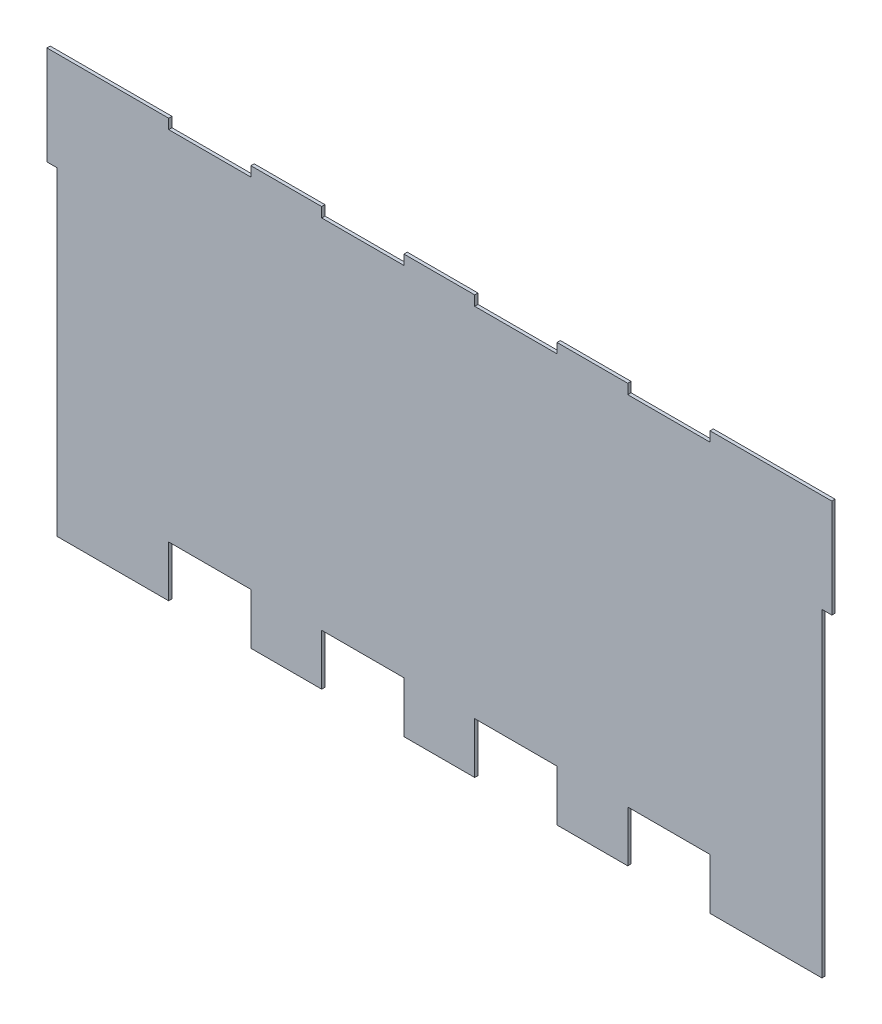
SolidWorks part; units mm, degrees
ref_plane "Front Plane" through (0, 0, 0) normal (0, 0, 1) x (1, 0, 0)
ref_plane "Top Plane" through (0, 0, 0) normal (0, 1, 0) x (1, 0, 0)
ref_plane "Right Plane" through (0, 0, 0) normal (1, 0, 0) x (0, 0, -1)
sketch "Sketch1" plane through (0, 0, 0) normal (0, 0, 1) x (1, 0, 0)
  line L1 (-232.5, -127) -> (232.5, -127)
  line L2 (-232.5, -127) -> (-232.5, 127)
  line L3 (-232.5, 127) -> (232.5, 127)
  line L4 (232.5, -127) -> (232.5, 127)
  line L5 (0, 127) -> (0, -127) construction
  line L6 (-232.5, 0) -> (232.5, 0) construction
  point P0 (0, 0)
  dimension "D1" = 465
  dimension "D2" = 254
extrude "Boss-Extrude1" add sketch "Sketch1" along normal blind 2
sketch "Sketch2" plane through (0, 0, 2) normal (0, 0, 1) x (1, 0, 0)
  line L0 (-232.5, -127) -> (232.5, -127) construction
  line L1 (-164.5, -133) -> (-114.5, -133)
  line L2 (-164.5, -133) -> (-164.5, -121)
  line L3 (-164.5, -121) -> (-114.5, -121)
  line L4 (-114.5, -133) -> (-114.5, -121)
  line L5 (-139.5, -121) -> (-139.5, -133) construction
  line L6 (-164.5, -127) -> (-114.5, -127) construction
  line L7 (232.5, 127) -> (-232.5, 127) construction
  line L8 (-71.5, -133) -> (-21.5, -133)
  line L9 (-71.5, -133) -> (-71.5, -121)
  line L10 (-71.5, -121) -> (-21.5, -121)
  line L11 (-21.5, -133) -> (-21.5, -121)
  line L12 (-46.5, -121) -> (-46.5, -133) construction
  line L13 (-71.5, -127) -> (-21.5, -127) construction
  line L14 (21.5, -133) -> (71.5, -133)
  line L15 (21.5, -133) -> (21.5, -121)
  line L16 (21.5, -121) -> (71.5, -121)
  line L17 (71.5, -133) -> (71.5, -121)
  line L18 (46.5, -121) -> (46.5, -133) construction
  line L19 (21.5, -127) -> (71.5, -127) construction
  line L20 (164.5, -133) -> (114.5, -133)
  line L21 (164.5, -133) -> (164.5, -121)
  line L22 (164.5, -121) -> (114.5, -121)
  line L23 (114.5, -133) -> (114.5, -121)
  line L24 (139.5, -121) -> (139.5, -133) construction
  line L25 (164.5, -127) -> (114.5, -127) construction
  line L26 (-164.5, 121) -> (-114.5, 121)
  line L27 (-164.5, 121) -> (-164.5, 133)
  line L28 (-164.5, 133) -> (-114.5, 133)
  line L29 (-114.5, 121) -> (-114.5, 133)
  line L30 (-139.5, 133) -> (-139.5, 121) construction
  line L31 (-164.5, 127) -> (-114.5, 127) construction
  line L33 (-71.5, 121) -> (-21.5, 121)
  line L34 (-71.5, 121) -> (-71.5, 133)
  line L35 (-71.5, 133) -> (-21.5, 133)
  line L36 (-21.5, 121) -> (-21.5, 133)
  line L37 (-46.5, 133) -> (-46.5, 121) construction
  line L38 (-71.5, 127) -> (-21.5, 127) construction
  line L39 (21.5, 121) -> (71.5, 121)
  line L40 (21.5, 121) -> (21.5, 133)
  line L41 (21.5, 133) -> (71.5, 133)
  line L42 (71.5, 121) -> (71.5, 133)
  line L43 (46.5, 133) -> (46.5, 121) construction
  line L44 (21.5, 127) -> (71.5, 127) construction
  line L45 (164.5, 121) -> (114.5, 121)
  line L46 (164.5, 121) -> (164.5, 133)
  line L47 (164.5, 133) -> (114.5, 133)
  line L48 (114.5, 121) -> (114.5, 133)
  line L49 (139.5, 133) -> (139.5, 121) construction
  line L50 (164.5, 127) -> (114.5, 127) construction
  point P0 (-139.5, -127)
  point P6 (-46.5, -127)
  point P10 (46.5, -127)
  point P14 (139.5, -127)
  point P18 (-139.5, 127)
  point P24 (-46.5, 127)
  point P33 (46.5, 127)
  point P37 (139.5, 127)
  point P41 (0, 0)
  point P43 (47.8891, 129.0274)
  dimension "D1" = 93
  dimension "D2" = 93
  dimension "D3" = 93
  dimension "D4" = 93
  dimension "D5" = 93
  dimension "D6" = 93
  dimension "D7" = 93
  dimension "D8" = 93
  dimension "D9" = 50
  dimension "D10" = 50
  dimension "D11" = 50
  dimension "D12" = 50
  dimension "D13" = 12
  dimension "D14" = 12
  dimension "D15" = 12
  dimension "D16" = 12
  dimension "D17" = 12
  dimension "D18" = 12
  dimension "D19" = 12
  dimension "D20" = 12
  dimension "D21" = 50
  dimension "D22" = 50
  dimension "D23" = 50
  dimension "D24" = 50
extrude "Cut-Extrude1" cut sketch "Sketch2" against normal blind 2
sketch "Sketch3" plane through (0, 0, 2) normal (0, 0, 1) x (1, 0, 0)
  line L1 (-232.5, 127) -> (-238.5, 127)
  line L2 (-232.5, 127) -> (-232.5, 67)
  line L3 (-232.5, 67) -> (-238.5, 67)
  line L4 (-238.5, 127) -> (-238.5, 67)
  line L5 (232.5, 127) -> (238.5, 127)
  line L6 (232.5, 127) -> (232.5, 67)
  line L7 (232.5, 67) -> (238.5, 67)
  line L8 (238.5, 127) -> (238.5, 67)
  dimension "D1" = 6
  dimension "D2" = 6
  dimension "D3" = 60
  dimension "D4" = 60
extrude "Boss-Extrude2" add sketch "Sketch3" against normal blind 2
sketch "Sketch4" plane through (0, 0, 2) normal (0, 0, 1) x (1, 0, 0)
  line L1 (-164.5, -121) -> (-114.5, -121)
  line L2 (-164.5, -121) -> (-164.5, -96)
  line L3 (-164.5, -96) -> (-114.5, -96)
  line L4 (-114.5, -121) -> (-114.5, -96)
  line L9 (21.5, -121) -> (71.5, -121)
  line L10 (21.5, -121) -> (21.5, -96)
  line L11 (21.5, -96) -> (71.5, -96)
  line L12 (71.5, -121) -> (71.5, -96)
  line L13 (114.5, -121) -> (164.5, -121)
  line L14 (114.5, -121) -> (114.5, -96)
  line L15 (114.5, -96) -> (164.5, -96)
  line L16 (164.5, -121) -> (164.5, -96)
  line L17 (-71.5, -121) -> (-21.5, -121)
  line L18 (-71.5, -121) -> (-71.5, -96)
  line L19 (-71.5, -96) -> (-21.5, -96)
  line L20 (-21.5, -121) -> (-21.5, -96)
  dimension "D1" = 50
  dimension "D2" = 50
  dimension "D3" = 50
  dimension "D4" = 50
  dimension "D5" = 25
  dimension "D6" = 25
  dimension "D7" = 25
  dimension "D8" = 25
extrude "Cut-Extrude2" cut sketch "Sketch4" against normal blind 2
